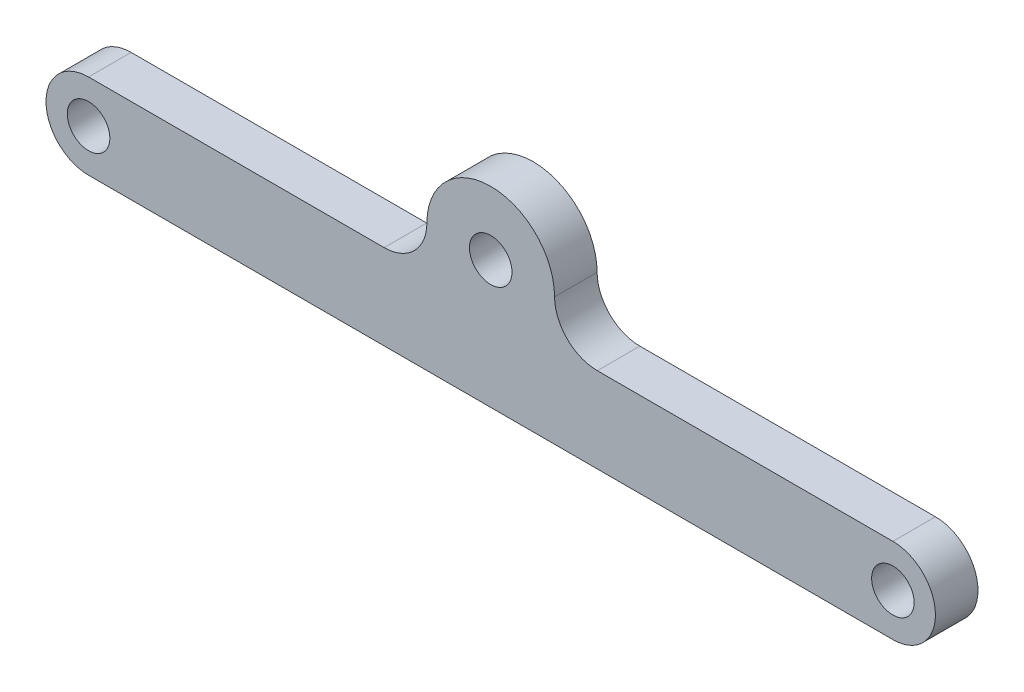
SolidWorks part; units mm, degrees
ref_plane "Front Plane" through (0, 0, 0) normal (0, 0, 1) x (1, 0, 0)
ref_plane "Top Plane" through (0, 0, 0) normal (0, 1, 0) x (1, 0, 0)
ref_plane "Right Plane" through (0, 0, 0) normal (1, 0, 0) x (0, 0, -1)
sketch "Sketch1" plane through (0, 0, 0) normal (0, 0, 1) x (1, 0, 0)
  line L0 (-120.015, 0) -> (120.015, 0) construction
  line L2 (149.479, 0) -> (-149.479, 0) construction
  line L3 (0, 0) -> (0, 25.4) construction
  line L4 (-120.015, 12.7) -> (-31.8097, 12.7)
  line L5 (-120.015, -12.7) -> (120.015, -12.7)
  line L6 (31.8097, 12.7) -> (120.015, 12.7)
  circle A0 centre (-120.015, 0) radius 6.35
  circle A1 centre (120.015, 0) radius 6.35
  circle A2 centre (0, 25.4) radius 6.35
  arc A3 (19.05, 25.4) -> (-19.05, 25.4) centre (0, 25.4) ccw
  arc A4 (-120.015, 12.7) -> (-120.015, -12.7) centre (-120.015, 0) ccw
  arc A5 (120.015, -12.7) -> (120.015, 12.7) centre (120.015, 0) ccw
  arc A6 (-19.05, 25.4) -> (-31.8097, 12.7) centre (-31.8097, 25.4599) cw
  arc A7 (19.05, 25.4) -> (31.8097, 12.7) centre (31.8097, 25.4599) ccw
  point P4 (0, 0)
  point P14 (31.8098, 12.6929)
  point P20 (-31.8097, 12.7)
  point P23 (19.05, 25.4547)
  point P25 (0, 0)
  point P26 (-19.05, 25.4547)
  point P27 (-31.8098, 12.7)
  dimension "D3" = 12.7
  dimension "D4" = 12.7
  dimension "D5" = 12.7
  dimension "D6" = 38.1
  dimension "D7" = 25.4
  dimension "D8" = 25.4
  dimension "D1" = 240.03
  dimension "D2" = 25.4
extrude "Boss-Extrude1" add sketch "Sketch1" along normal blind 12.7
